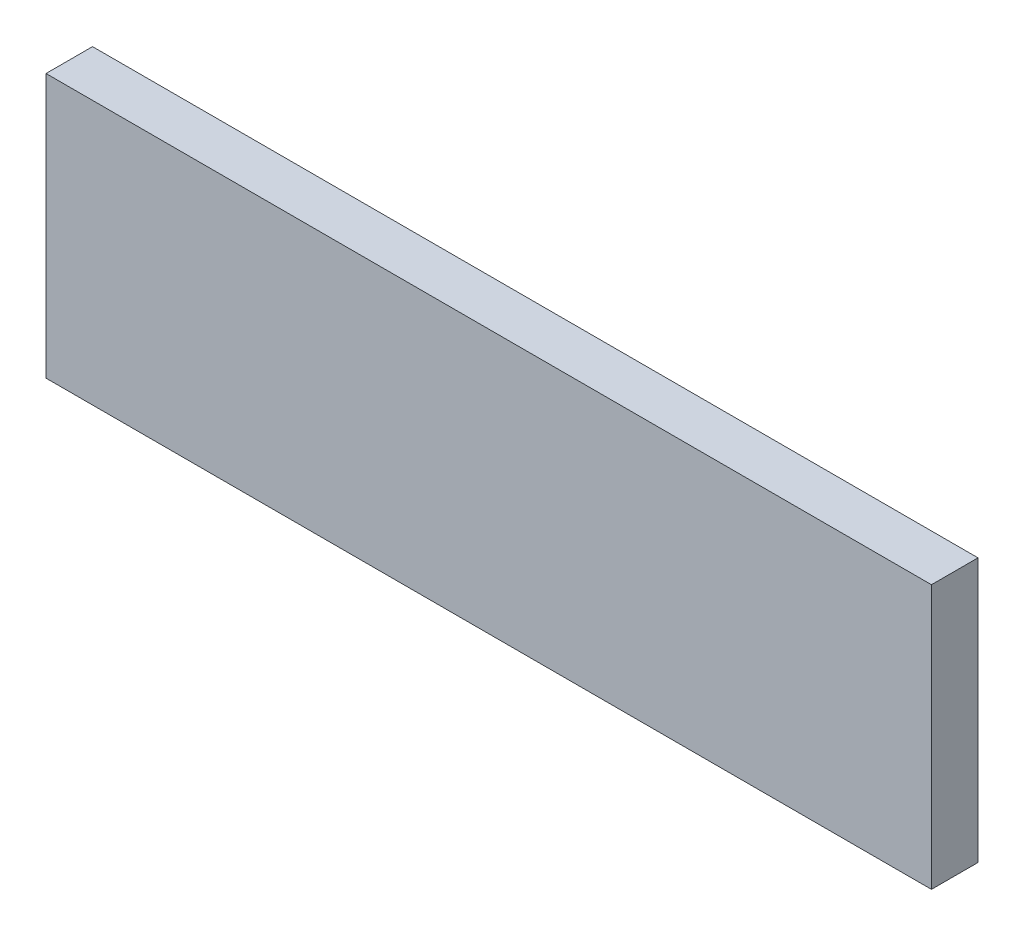
SolidWorks part; units mm, degrees
ref_plane "Front Plane" through (0, 0, 0) normal (0, 0, 1) x (1, 0, 0)
ref_plane "Top Plane" through (0, 0, 0) normal (0, 1, 0) x (1, 0, 0)
ref_plane "Right Plane" through (0, 0, 0) normal (1, 0, 0) x (0, 0, -1)
sketch "Sketch1" plane through (0, 0, 0) normal (0, 0, 1) x (1, 0, 0)
  line L0 (0.0127, 5.6871) -> (19.0373, 5.6871)
  line L1 (19.0373, 5.6871) -> (19.0373, 0.0178)
  line L2 (19.0373, 0.0178) -> (0.0127, 0.0178)
  line L3 (0.0127, 0.0178) -> (0.0127, 5.6871)
extrude "Component_Outline" add sketch "Sketch1" along normal blind 1 separate body
sketch3d "3DSketch1"
  line L0 (0, 0, 0) -> (1, 0, 0)
  line L1 (0, 0, 0) -> (0, 1, 0)
  line L2 (0, 0, 0) -> (0, 0, 1)
  point P0 (0, 0, 0)
